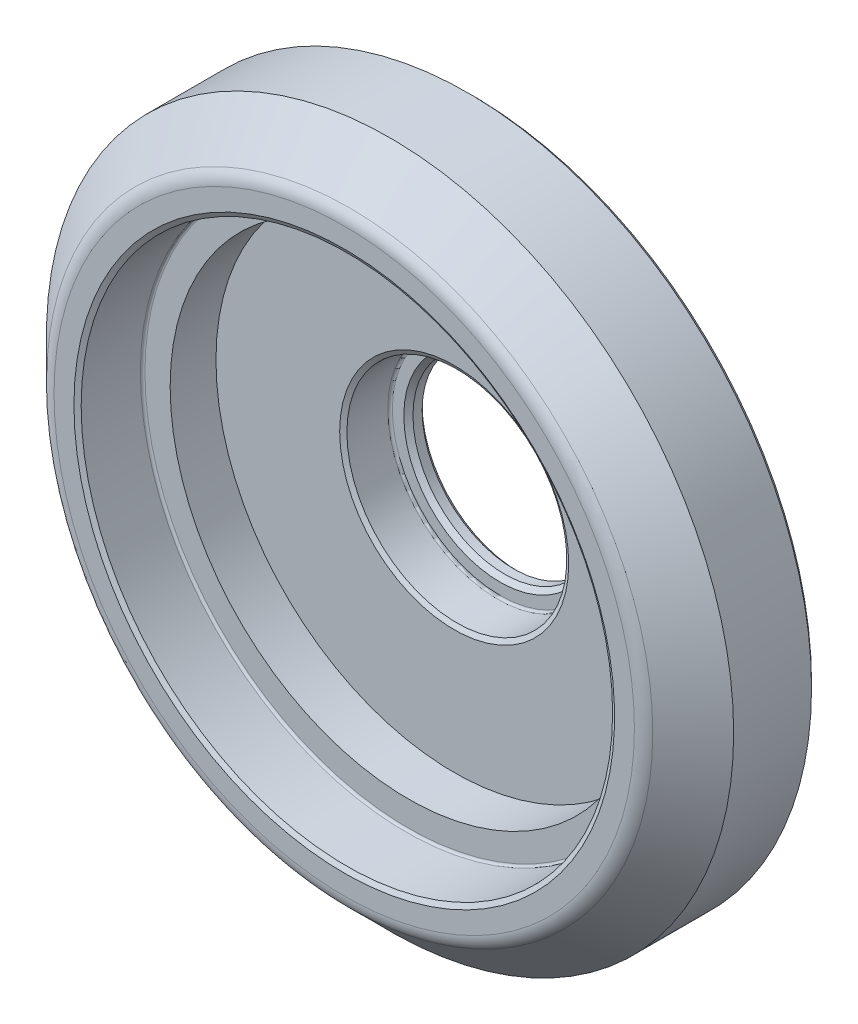
SolidWorks part; units mm, degrees
material "A2017"
ref_plane "正面" through (0, 0, 0) normal (0, 0, 1) x (1, 0, 0)
ref_plane "平面" through (0, 0, 0) normal (0, 1, 0) x (1, 0, 0)
ref_plane "右側面" through (0, 0, 0) normal (1, 0, 0) x (0, 0, -1)
sketch "ｽｹｯﾁ1" plane through (0, 0, 0) normal (1, 0, 0) x (0, 0, -1)
  line L0 (-9, 37.5) -> (-14, 32.5)
  line L1 (-14, 32.5) -> (-14, 29)
  line L2 (-14, 29) -> (-7, 29)
  line L3 (-7, 29) -> (-7, 26)
  line L4 (-7, 26) -> (-2, 26)
  line L5 (-2, 26) -> (-2, 12)
  line L6 (-9, 37.5) -> (0, 37.5)
  line L7 (0, 37.5) -> (0, 17.5)
  line L8 (0, 17.5) -> (3, 17.5)
  line L9 (3, 17.5) -> (3, 12)
  line L10 (3, 12) -> (-2, 12)
  line L11 (-26.8995, 0) -> (7.6593, 0) construction
  point P14 (-14, 33.5483)
  point P15 (-8.6876, 29)
  point P16 (-4.3977, 23.5053)
  point P17 (0, 19.5307)
  dimension "D1" = 75
  dimension "D2" = 14
  dimension "D3" = 45
  dimension "D4" = 58
  dimension "D5" = 5
  dimension "D6" = 24
  dimension "D7" = 35
  dimension "D8" = 3
  dimension "D9" = 7
  dimension "D10" = 5
  dimension "D11" = 52
revolve "回転1" add sketch "ｽｹｯﾁ1" angle 360 about L11
fillet "ﾌｨﾚｯﾄ1" radius 2 2 edges at (17.5, 0, 0) (32.5, 0, 14)
chamfer "面取り1" distance 0.5 angle 30 1 edges at (29, 0, 14)
chamfer "面取り2" distance 0.5 angle 30 1 edges at (12, 0, 2)
sketch "ｽｹｯﾁ2" plane through (0, 0, -3) normal (0, 0, -1) x (-1, 0, 0)
  circle A1 centre (0, 0) radius 17.5
  circle A2 centre (0, 0) radius 17.5
  circle A4 centre (0, 0) radius 10
  circle A5 centre (0, 0) radius 10
  dimension "D1" = 0
  dimension "D2" = 2
extrude "ﾎﾞｽ - 押し出し1" add sketch "ｽｹｯﾁ2" along normal blind 2
chamfer "面取り3" distance 0.5 angle 45 2 edges at (-10, 0, -3) (-10, 0, -5)
chamfer "面取り4" distance 0.5 angle 45 2 edges at (37.5, 0, 0) (-17.5, 0, -5)
fillet "ﾌｨﾚｯﾄ2" radius 0.25 2 edges at (29, 0, 7) (12, 0, -3)
